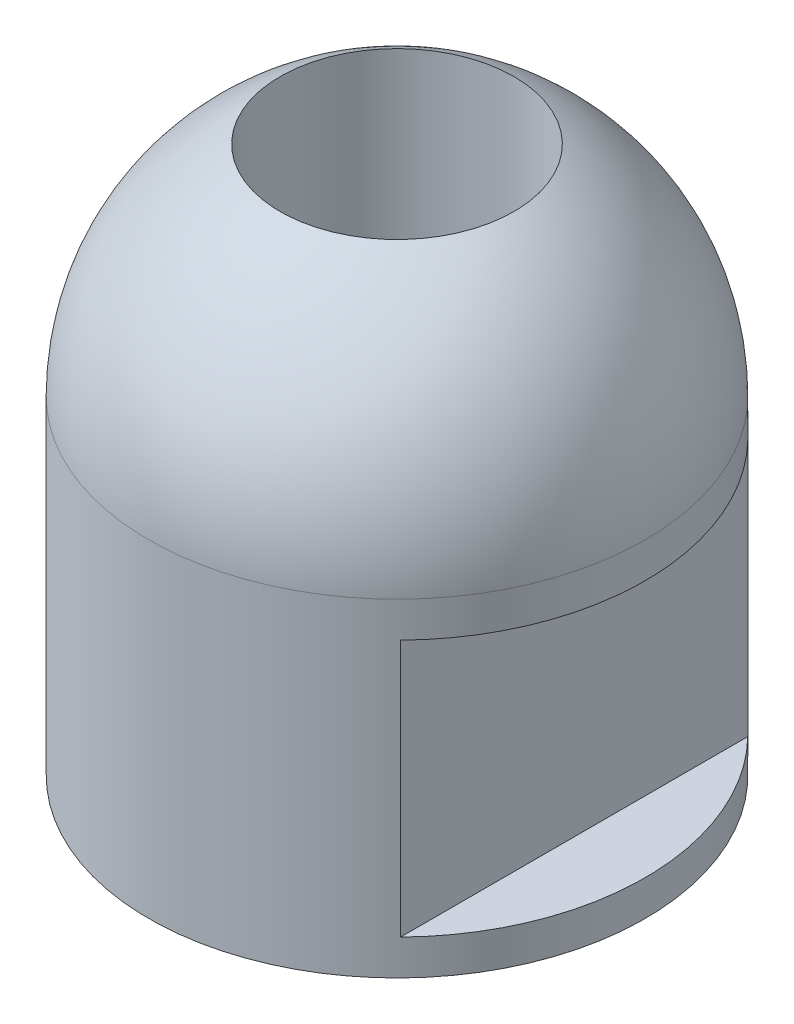
SolidWorks part; units mm, degrees
ref_plane "Front Plane" through (0, 0, 0) normal (0, 0, 1) x (1, 0, 0)
ref_plane "Top Plane" through (0, 0, 0) normal (0, 1, 0) x (1, 0, 0)
ref_plane "Right Plane" through (0, 0, 0) normal (1, 0, 0) x (0, 0, -1)
sketch "Sketch1" plane through (0, 0, 0) normal (0, 0, 1) x (1, 0, 0)
  line L0 (0, 0) -> (0, 8.1277)
  line L1 (0, 0) -> (3.5, 0)
  line L2 (3.5, 0) -> (3.5, 4.6277)
  line L4 (0, 8.1277) -> (0, 11.2857) construction
  line L5 (0, 7.5) -> (2, 7.5) construction
  arc A0 (3.5, 4.6277) -> (0, 8.1277) centre (0, 4.6277) ccw
  dimension "D1" = 3.5
  dimension "D2" = 7.5
  dimension "D3" = 4
revolve "Revolve1" add sketch "Sketch1" angle 360 about L4
hole_wizard "Tap Drill for M4x0.7 Tap1" positions "Sketch4" profile "Sketch3" hole size "M4x0.7" standard "ANSI Metric" end condition through all
sketch "Sketch4" plane through (0, 0, 0) normal (0, -1, 0) x (-1, 0, 0)
  point P0 (0, 0)
sketch "Sketch3" plane through (0, 0, 0) normal (1, 0, 0) x (0, 0, -1)
  line L0 (0, 0) -> (0, 8.1277)
  line L1 (0, 8.1277) -> (1.65, 8.1277)
  line L2 (1.65, 8.1277) -> (1.65, 0)
  line L5 (1.65, 0) -> (0, 0)
  line L11 (0, -6.35) -> (0, 107.95) construction
  dimension "Thru Hole Dia." = 3.3
  dimension "Thru Hole Depth" = 8.1277
sketch "Sketch5" plane through (0, 0, 0) normal (0, 0, 1) x (1, 0, 0)
  line L0 (3.5, 0.5) -> (2.5, 0.5)
  line L1 (3.5, 0) -> (3.5, 4.6277) construction
  line L2 (2.5, 0.5) -> (2.5, 4.1277)
  line L3 (2.5, 4.1277) -> (3.5, 4.1277)
  line L4 (3.5, 4.1277) -> (3.5, 0.5)
  line L5 (0, 0) -> (0, 8.9579) construction
  line L6 (-3.5, 0) -> (3.5, 0) construction
  line L7 (3.5, 4.6277) -> (-3.5, 4.6277) construction
  line L8 (-3.5, 4.1277) -> (-3.5, 0.5)
  line L9 (-2.5, 4.1277) -> (-3.5, 4.1277)
  line L10 (-2.5, 0.5) -> (-2.5, 4.1277)
  line L11 (-3.5, 0.5) -> (-2.5, 0.5)
  dimension "D1" = 5
  dimension "D2" = 0.5
  dimension "D3" = 0.5
extrude "Cut-Extrude1" cut sketch "Sketch5" against normal through all both and the other way through all
